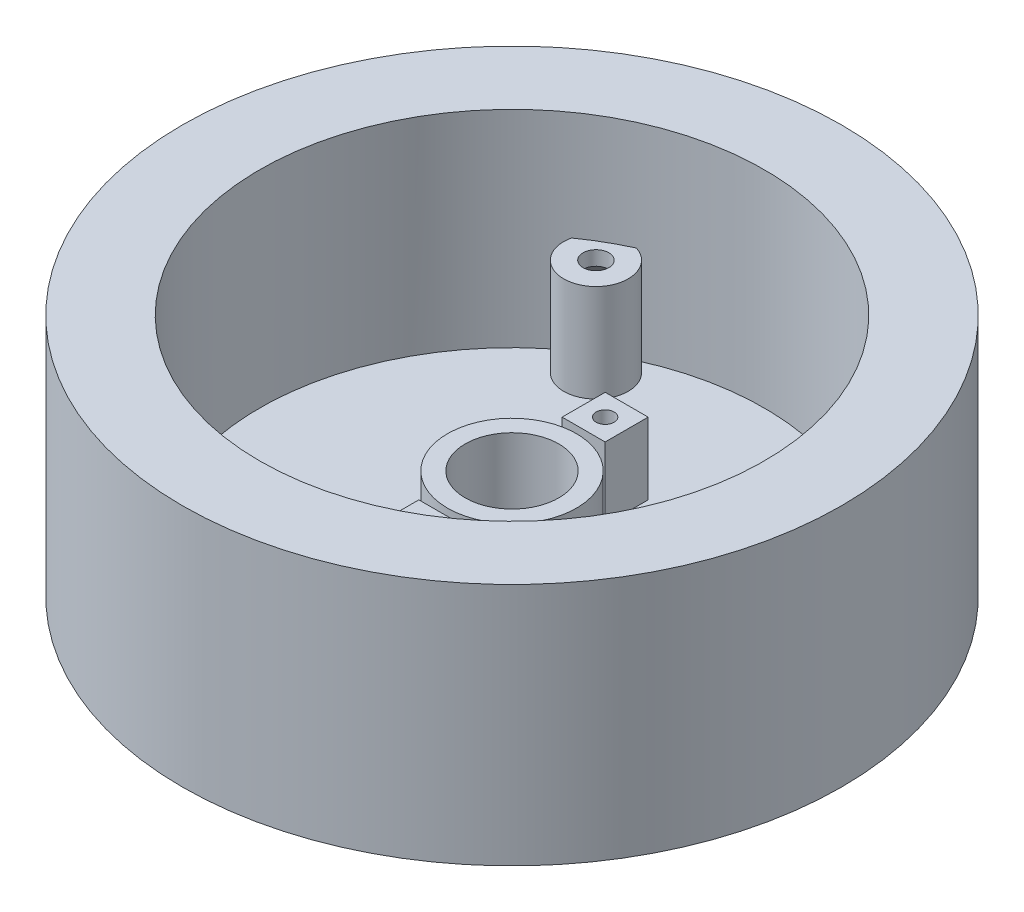
SolidWorks part; units mm, degrees
ref_plane "Front Plane" through (0, 0, 0) normal (0, 0, 1) x (1, 0, 0)
ref_plane "Top Plane" through (0, 0, 0) normal (0, 1, 0) x (1, 0, 0)
ref_plane "Right Plane" through (0, 0, 0) normal (1, 0, 0) x (0, 0, -1)
sketch "Sketch1" plane through (0, 0, 0) normal (0, 1, 0) x (1, 0, 0)
  circle A0 centre (0, 0) radius 23
  dimension "D1" = 46
extrude "Boss-Extrude1" add sketch "Sketch1" along normal blind 17
shell "Shell1" thickness 2.6
sketch "Sketch2" plane through (0, 0, 0) normal (0, -1, 0) x (1, 0, 0)
  line L0 (0, -23) -> (0, 5)
  line L1 (6, -18) -> (-6, -18)
  line L2 (-6, -18) -> (-6, 5)
  line L3 (-6, 5) -> (6, 5)
  line L4 (6, -18) -> (6, 5)
  circle A0 centre (0, 0) radius 23 construction
  point P9 (0, -18)
  dimension "D1" = 28
  dimension "D2" = 23
  dimension "D3" = 6
extrude "Boss-Extrude2" [suppressed] add sketch "Sketch2" along normal blind 6 contours L3 L2 L1 L0 | L1 L4 L3 L0
sketch "Sketch3" [suppressed] plane through (0, 0, -18) normal (0, 0, -1) x (-1, 0, 0)
  line L0 (-6, -3) -> (-4, -3)
  line L2 (-6, -6) -> (-6, 0) construction
  line L3 (-4, -3) -> (-4, 0)
  line L4 (-6, 0) -> (6, 0) construction
  line L5 (-4, 0) -> (-6, 0)
  line L6 (-6, 0) -> (-6, -3)
  line L7 (0, -6) -> (0, 0) construction
  line L8 (-6, -6) -> (6, -6) construction
  line L9 (4, 0) -> (6, 0)
  line L10 (4, -3) -> (4, 0)
  line L11 (6, -3) -> (4, -3)
  line L12 (6, 0) -> (6, -3)
  dimension "D1" = 2
extrude "Cut-Extrude1" [suppressed] cut sketch "Sketch3" against normal through all
sketch "Sketch4" plane through (0, 2.6, 0) normal (0, 1, 0) x (1, 0, 0)
  circle A0 centre (0, 0) radius 4.5
  dimension "D1" = 9
extrude "Boss-Extrude3" add sketch "Sketch4" along normal blind 5
sketch "Sketch5" plane through (0, 7.6, 0) normal (0, 1, 0) x (1, 0, 0)
  circle A0 centre (0, 0) radius 3.265
  dimension "D1" = 6.53
extrude "Cut-Extrude2" cut sketch "Sketch5" against normal through all
ref_plane "Plane1" [suppressed] through (0, 0, 5) normal (0, 0, 1) x (1, 0, 0)
sketch "Sketch7" [suppressed] plane through (0, 0, 5) normal (0, 0, 1) x (1, 0, 0)
  line L0 (-1.91, -4.3) -> (-1.91, -1.7)
  line L1 (-1.91, -4.3) -> (1.91, -4.3)
  line L2 (-1.91, -1.7) -> (1.91, -1.7)
  line L3 (1.91, -4.3) -> (1.91, -1.7)
  line L4 (0, -6) -> (0, 0) construction
  line L5 (-1.91, -3) -> (1.91, -3) construction
  line L6 (-6, -6) -> (6, -6) construction
  point P8 (0, -3)
  point P10 (0, -3)
  dimension "D1" = 3.82
  dimension "D2" = 2.6
extrude "Cut-Extrude3" [suppressed] cut sketch "Sketch7" against normal blind 1.71
ref_plane "Plane2" [suppressed] through (0, -3, 0) normal (0, -1, 0) x (-1, 0, 0)
sketch "Sketch8" [suppressed] plane through (0, -3, 0) normal (0, -1, 0) x (-1, 0, 0)
  line L0 (-4, -1.3082) -> (-4, -2.5)
  line L1 (-4, -1.3082) -> (4.0117, -1.3082)
  line L2 (-3.9936, -3.2831) -> (4.0181, -3.2831)
  line L3 (4.0117, -1.3082) -> (4.0117, -2.5)
  line L4 (-4, -5) -> (-4, 18) construction
  line L7 (-3.9936, -3.2831) -> (-4, -2.5)
  line L8 (4.0181, -3.2831) -> (4.0117, -2.5)
extrude "Boss-Extrude4" [suppressed] add sketch "Sketch8" against normal blind 3
hole_wizard "CSK SLOT for M2 Countersunk Flat Head Screw1" [suppressed] positions "3DSketch1" profile "Sketch9" size "M2" standard "ISO"
sketch3d "3DSketch1"
  line L0 (22.9111, 13, 2.0208) -> (22.9111, 0, 2.0208) construction
  circle A0 centre (0, 0, 0) radius 23 construction
  point P0 (22.9111, 13, 2.0208)
  point P5 (0, 23, 0)
  dimension "D1" = 13
sketch "Sketch9" plane through (22.9111, 13, 2.0208) normal (0, 1, 0) x (0.0879, 0, -0.9961)
  line L0 (0, 0) -> (0, 5.721)
  line L1 (0, 5.721) -> (1.2, 5)
  line L2 (1.2, 5) -> (1.2, 2)
  line L3 (1.2, 2) -> (3.2, 0)
  line L5 (3.2, 0) -> (0, 0)
  line L6 (-1.2, 2) -> (-3.2, 0) construction
  line L10 (0, 5.721) -> (-1.2, 5) construction
  line L11 (0, -6.35) -> (0, 107.95) construction
  dimension "Hole Dia." = 2.4
  dimension "Hole Depth" = 5
  dimension "Near C'Sink Dia." = 6.4
  dimension "Near C'Sink Angle" = 90
  dimension "Drill Angle" = 118
pattern_circular "CirPattern1" [suppressed] count 3 over 360
sketch "Sketch10" [suppressed] plane through (0, 0, 3.29) normal (0, 0, 1) x (1, 0, 0)
  line L0 (-1.91, -3) -> (-1.55, -3) construction
  line L1 (-1.91, -1.7) -> (-1.91, -4.3) construction
  line L2 (1.91, -4.3) -> (1.91, -1.7) construction
  line L4 (1.55, -3.9) -> (-1.55, -3.9)
  line L5 (1.55, -3.9) -> (1.55, -1.7)
  line L6 (1.55, -1.7) -> (-1.55, -1.7)
  line L7 (-1.55, -3.9) -> (-1.55, -1.7)
  line L8 (1.91, -1.7) -> (-1.91, -1.7) construction
  line L11 (1.55, -3) -> (1.91, -3) construction
  point P6 (0, -3)
  point P7 (0, -3)
  dimension "D1" = 3.1
extrude "Cut-Extrude4" [suppressed] cut sketch "Sketch10" against normal blind 3
sketch "Sketch11" [suppressed] plane through (0, -3.9, 0) normal (0, 1, 0) x (1, 0, 0)
  line L0 (1.55, -3.29) -> (-1.55, -3.29)
  line L1 (1.55, -3.29) -> (1.55, -2.102)
  line L2 (-1.55, -3.29) -> (-1.55, -2.102)
  line L3 (1.55, -2.102) -> (-1.55, -2.102)
extrude "Boss-Extrude6" [suppressed] add sketch "Sketch11" against normal up to next
fillet "Fillet1" [suppressed] radius 2
hole_wizard "CSK SLOT for M1.6 Countersunk Flat Head Screw1" [suppressed] positions "Sketch12" profile "Sketch13" size "M1.6" standard "ISO"
sketch "Sketch12" plane through (0, 2.6, 0) normal (0, 1, 0) x (1, 0, 0)
  line L7 (0, 0) -> (12.3, 6.5) construction
  line L8 (12.3, 6.5) -> (12.3, 0) construction
  line L9 (12.3, 0) -> (0, 0) construction
  line L11 (0, 0) -> (-12.3, -14) construction
  line L12 (-12.3, -14) -> (0, -14) construction
  line L13 (0, -14) -> (0, 0) construction
  point P42 (12.3, 6.5)
  point P45 (-12.3, -14)
  dimension "D1" = 12.3
  dimension "D3" = 6.5
  dimension "D4" = 12.3
  dimension "D5" = 14
sketch "Sketch13" plane through (-12.3, 2.6, 14) normal (1, 0, 0) x (0, 0, 1)
  line L0 (0, 0) -> (0, 2.6)
  line L1 (0, 2.6) -> (0.9, 2.6)
  line L2 (0.9, 2.6) -> (0.9, 0.9)
  line L3 (0.9, 0.9) -> (1.8, 0)
  line L5 (1.8, 0) -> (0, 0)
  line L6 (-0.9, 0.9) -> (-1.8, 0) construction
  line L11 (0, -6.35) -> (0, 107.95) construction
  dimension "Thru Hole Dia." = 1.8
  dimension "Thru Hole Depth" = 2.6
  dimension "Near C'Sink Dia." = 3.6
  dimension "Near C'Sink Angle" = 90
hole_wizard "M1.6 Tapped Hole1" positions "Sketch18" profile "Sketch19" tap size "M1.6" standard "ISO" end condition through all
sketch "Sketch18" plane through (0, 0, 0) normal (0, -1, 0) x (-1, 0, 0)
  line L0 (0, -6.498) -> (0, 0)
  line L3 (0, 0) -> (0, 6.498)
  point P0 (0, 6.498)
  point P2 (0, -6.498)
  dimension "D1" = 6.498
sketch "Sketch19" plane through (0, 0, -6.498) normal (1, 0, 0) x (0, 0, -1)
  line L0 (0, 0) -> (0, 17)
  line L1 (0, 17) -> (0.625, 17)
  line L2 (0.625, 17) -> (0.625, 0)
  line L5 (0.625, 0) -> (0, 0)
  line L11 (0, -6.35) -> (0, 107.95) construction
  dimension "Thru Tap Drill Dia." = 1.25
  dimension "Thru Tap Drill Depth" = 17
cosmetic thread "Hole Thread1" parameters "D2"=1.6
cosmetic thread "Hole Thread2" parameters "D2"=1.6
sketch "Sketch20" plane through (0, 2.6, 0) normal (0, 1, 0) x (1, 0, 0)
  line L6 (0, 0) -> (6.4738, 0)
  line L9 (-1.5, -7.998) -> (1.5, -7.998)
  line L10 (-1.5, -7.998) -> (-1.5, -4.998)
  line L11 (-1.5, -4.998) -> (1.5, -4.998)
  line L12 (1.5, -7.998) -> (1.5, -4.998)
  line L13 (-1.5, -7.998) -> (1.5, -4.998) construction
  line L14 (-1.5, -4.998) -> (1.5, -7.998) construction
  line L15 (-1.5, 4.998) -> (1.5, 4.998)
  line L16 (1.5, 7.998) -> (1.5, 4.998)
  line L17 (-1.5, 7.998) -> (1.5, 7.998)
  line L18 (-1.5, 7.998) -> (-1.5, 4.998)
  point P0 (0, -6.498)
  circle M6 centre (0, 6.498) radius 0.625
  circle M7 centre (0, -6.498) radius 0.625
  dimension "D1" = 3
  dimension "D2" = 3
extrude "Boss-Extrude8" add sketch "Sketch20" along normal blind 5 contours L9 L12 L11 L10 M7 | L17 L18 L15 L16 M6
ref_plane "Plane3" through (0, 17, 0) normal (0, 1, 0) x (1, 0, 0)
sketch "Sketch21" plane through (0, 17, 0) normal (0, 1, 0) x (1, 0, 0)
  circle A0 centre (0, 0) radius 20.4
  circle A1 centre (0, 0) radius 17.6
  dimension "D1" = 35.2
extrude "Boss-Extrude9" [suppressed] add sketch "Sketch21" against normal blind 7.6
sketch "Sketch22" plane through (0, 2.6, 0) normal (0, 1, 0) x (1, 0, 0)
  circle A0 centre (0, 0) radius 20.4
  circle A1 centre (0, 0) radius 17.6
  dimension "D1" = 35.2
extrude "Boss-Extrude10" add sketch "Sketch22" along normal up to surface (14.4 mm away) up to face at (0, 17, 20.4)
sketch "Sketch23" plane through (0, 0, 0) normal (0, -1, 0) x (1, 0, 0)
  line L0 (0, 0) -> (16, 0)
  point P4 (16, 0)
  point P8 (-8, -13.8564)
  point P9 (-8, 13.8564)
  point P10 (0, 0)
  dimension "D1" = 16
  dimension "D2" = 3
sketch "Sketch24" plane through (0, 2.6, 0) normal (0, 1, 0) x (1, 0, 0)
  circle A0 centre (-8, 13.8564) radius 2.25
  circle A1 centre (16, 0) radius 2.25
  circle A2 centre (-8, -13.8564) radius 2.25
  point P11 (0, 0)
  dimension "D1" = 4.5
  dimension "D2" = 3
extrude "Boss-Extrude11" add sketch "Sketch24" along normal offset from surface (6.8 mm away) 7.6 up to face at (0, 17, 23)
hole_wizard "CSK SLOT for M1.6 Countersunk Flat Head Screw2" positions "Sketch25" profile "Sketch26" size "M1.6" standard "ISO" slot yes end condition through all
sketch "Sketch25" plane through (0, 0, 0) normal (0, -1, 0) x (-1, 0, 0)
  point P0 (8, -13.8564)
  point P3 (8, 13.8564)
  point P6 (-16, 0)
sketch "Sketch26" plane through (-8, 0, 13.8564) normal (1, 0, 0) x (0, 0, -1)
  line L0 (0, 0) -> (0, 17)
  line L1 (0, 17) -> (0.9, 17)
  line L2 (0.9, 17) -> (0.9, 8.4)
  line L3 (0.9, 8.4) -> (1.8, 7.5)
  line L4 (1.8, 7.5) -> (1.8, 0)
  line L6 (1.8, 0) -> (0, 0)
  line L7 (-0.9, 8.4) -> (-1.8, 7.5) construction
  line L11 (0, -6.35) -> (0, 107.95) construction
  dimension "Thru Hole Dia." = 1.8
  dimension "Thru Hole Depth" = 17
  dimension "C'Sink Dia." = 3.6
  dimension "C'Sink Angle" = 90
  dimension "Head Clearance" = 7.5
